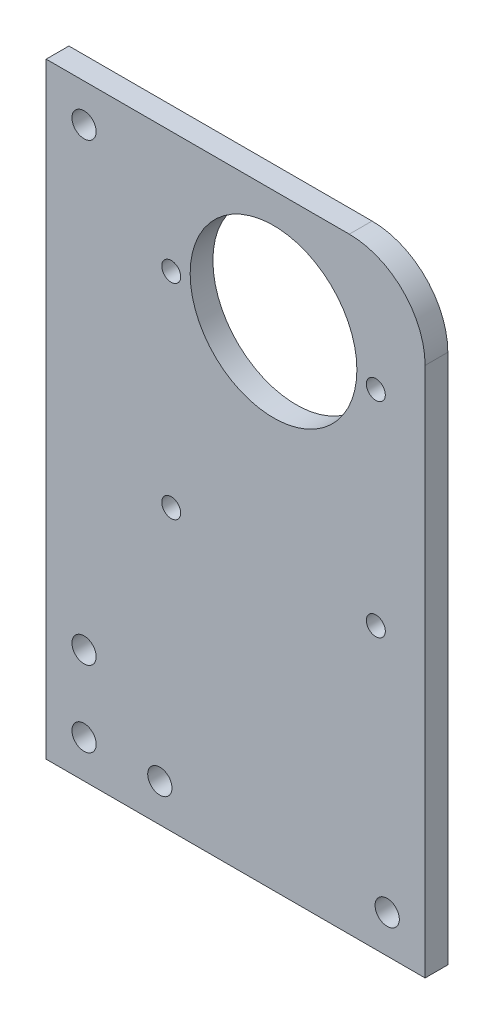
SolidWorks part; units mm, degrees
ref_plane "Front Plane" through (0, 0, 0) normal (0, 0, 1) x (1, 0, 0)
ref_plane "Top Plane" through (0, 0, 0) normal (0, 1, 0) x (1, 0, 0)
ref_plane "Right Plane" through (0, 0, 0) normal (1, 0, 0) x (0, 0, -1)
sketch "ｽｹｯﾁ1" plane through (0, 0, 0) normal (0, 0, 1) x (1, 0, 0)
  line L1 (25, -40) -> (-25, -40)
  line L2 (25, -40) -> (25, 40)
  line L3 (25, 40) -> (-25, 40)
  line L4 (-25, -40) -> (-25, 40)
  line L5 (25, -40) -> (-25, 40) construction
  line L6 (25, 40) -> (-25, -40) construction
  point P0 (0, 0)
  dimension "D1" = 50
  dimension "D2" = 80
extrude "ﾎﾞｽ - 押し出し1" add sketch "ｽｹｯﾁ1" along normal blind 3
sketch "ｽｹｯﾁ2" plane through (0, 0, 3) normal (0, 0, 1) x (1, 0, 0)
  line L0 (-25, -40) -> (25, -40) construction
  line L1 (-25, 40) -> (-25, -40) construction
  line L2 (25, 40) -> (-25, 40) construction
  line L3 (-25, 40) -> (-25, -40) construction
  line L4 (25, 40) -> (-25, 40) construction
  line L5 (25, -40) -> (25, 40) construction
  line L6 (-25, -40) -> (25, -40) construction
  circle A0 centre (5, 25) radius 11
  circle A1 centre (18.5, 24) radius 1.25
  circle A2 centre (-20, 35) radius 1.6
  circle A4 centre (-20, -25) radius 1.6
  circle A5 centre (-8.5, 24) radius 1.25
  circle A6 centre (18.5, -3) radius 1.25
  circle A7 centre (-20, -35) radius 1.6
  circle A8 centre (-10, -35) radius 1.6
  circle A9 centre (20, -35) radius 1.6
  circle A10 centre (-8.5, -3) radius 1.25
  dimension "D1" = 22
  dimension "D3" = 2.5
  dimension "D4" = 3.2
  dimension "D5" = 5
  dimension "D6" = 13.5
  dimension "D7" = 1
  dimension "D8" = 5
  dimension "D9" = 3.2
  dimension "D10" = 15
  dimension "D11" = 5
  dimension "D12" = 30
  dimension "D2" = 15
  dimension "D14" = 2.5
  dimension "D15" = 1
  dimension "D16" = 13.5
  dimension "D17" = 2.5
  dimension "D18" = 27
  dimension "D19" = 13.5
  dimension "D20" = 3.2
  dimension "D21" = 5
  dimension "D22" = 5
  dimension "D23" = 3.2
  dimension "D24" = 5
  dimension "D25" = 5
  dimension "D26" = 3.2
  dimension "D27" = 5
  dimension "D28" = 10
  dimension "D29" = 27
  dimension "D30" = 2.5
  dimension "D31" = 13.5
  dimension "D13" = 30
extrude "ｶｯﾄ - 押し出し1" cut sketch "ｽｹｯﾁ2" against normal through all
fillet "ﾌｨﾚｯﾄ1" radius 10 1 edges at (25, 40, 1.5)
